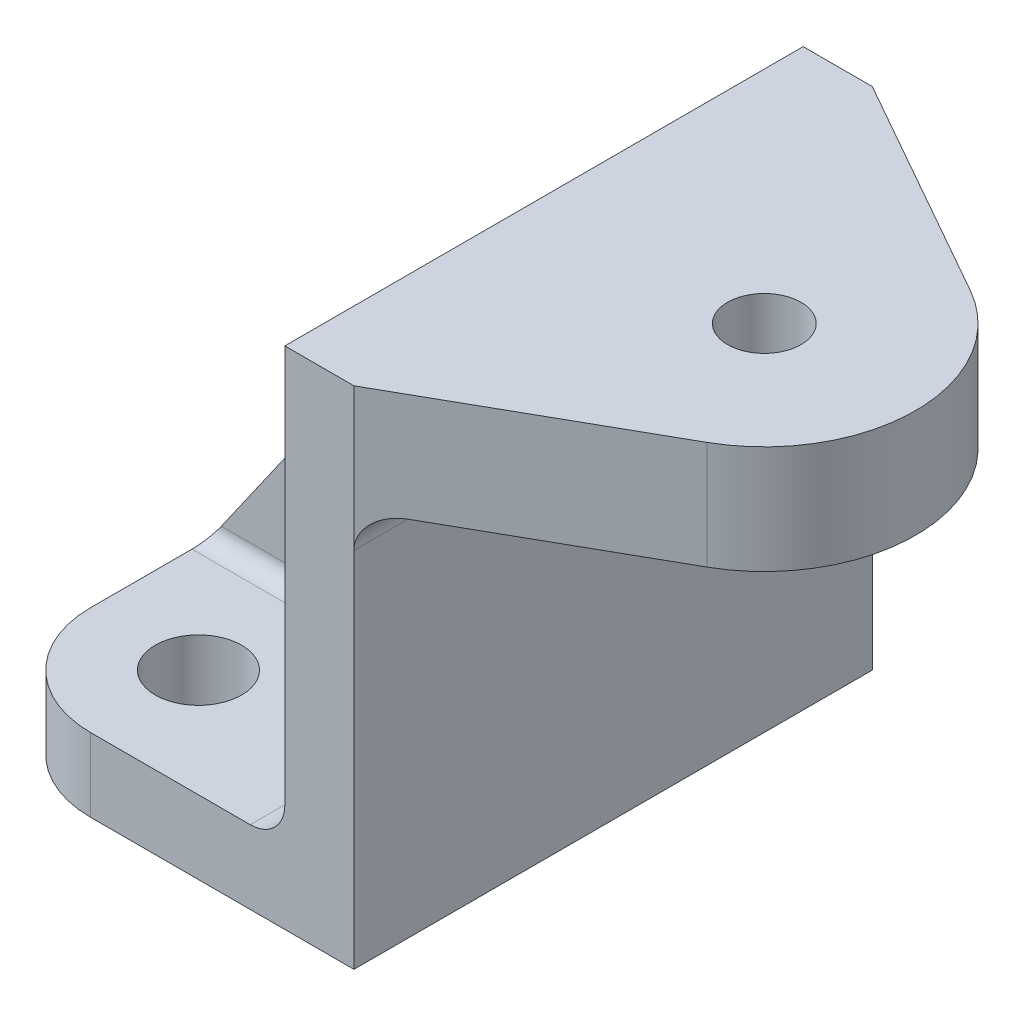
SolidWorks part; units mm, degrees
ref_plane "Front Plane" through (0, 0, 0) normal (0, 0, 1) x (1, 0, 0)
ref_plane "Top Plane" through (0, 0, 0) normal (0, 1, 0) x (1, 0, 0)
ref_plane "Right Plane" through (0, 0, 0) normal (1, 0, 0) x (0, 0, -1)
sketch "Sketch1" plane through (0, 0, 0) normal (0, 1, 0) x (1, 0, 0)
  line L1 (-30.5, 60) -> (30.5, 60)
  line L2 (-55.5, 35) -> (-55.5, -35)
  line L3 (-30.5, -60) -> (30.5, -60)
  line L4 (30.5, 60) -> (30.5, -60)
  circle A0 centre (-30.5, 35) radius 10
  circle A1 centre (-30.5, -35) radius 10
  arc A2 (-30.5, -60) -> (-55.5, -35) centre (-30.5, -35) cw
  arc A3 (-30.5, 60) -> (-55.5, 35) centre (-30.5, 35) ccw
  point P4 (-55.5, 0)
  point P5 (0, -60)
  point P11 (0, 0)
  point P16 (-55.5, 60)
  dimension "D3" = 20
  dimension "D4" = 25
  dimension "D5" = 25
  dimension "D6" = 25
  dimension "D7" = 25
  dimension "D1" = 120
  dimension "D2" = 86
extrude "Boss-Extrude1" add sketch "Sketch1" along normal blind 17
sketch "Sketch2" plane through (0, 17, 0) normal (0, 1, 0) x (1, 0, 0)
  line L0 (-30.5, -60) -> (30.5, -60) construction
  line L1 (30.5, 60) -> (14.5, 60)
  line L2 (30.5, 60) -> (30.5, -60)
  line L3 (30.5, -60) -> (14.5, -60)
  line L4 (14.5, 60) -> (14.5, -60)
  dimension "D1" = 16
extrude "Boss-Extrude2" add sketch "Sketch2" along normal blind 100
fillet "Fillet1" radius 8 1 edges at (14.5, 17, 0)
ref_plane "Plane1" through (0, 117, 0) normal (0, 1, 0) x (1, 0, 0)
sketch "Sketch3" plane through (0, 117, 0) normal (0, 1, 0) x (1, 0, 0)
  line L0 (30.5, -60) -> (30.5, 60) construction
  line L1 (30.5, 60) -> (82.728, 30.4663)
  line L2 (30.5, -60) -> (82.728, -30.4663)
  line L3 (30.5, -60) -> (30.5, 60)
  arc A0 (82.728, -30.4663) -> (82.728, 30.4663) centre (65.5, 0) ccw
  circle A1 centre (65.5, 0) radius 8.5
  dimension "D1" = 70
  dimension "D2" = 35
  dimension "D3" = 17
extrude "Boss-Extrude3" add sketch "Sketch3" against normal blind 25
ref_plane "Plane2" through (0, 0, 0) normal (0, 0, 1) x (1, 0, 0)
sketch "Sketch6" plane through (0, 0, 0) normal (0, 0, 1) x (1, 0, 0)
  line L0 (14.5, 117) -> (-55.5, 17)
rib "Rib2" sketch "Sketch6" sketch "Sketch6" thickness 15 extrusion direction parallel to sketch draft on no parameters "D1"=15
fillet "Fillet2" radius 4 6 edges at (-24.5, 17, -7.5) (12.1569, 19.3431, -7.5) (-24.5, 17, 7.5) (12.1569, 19.3431, 7.5) (14.5, 71, -7.5) (14.5, 71, 7.5)
fillet "Fillet3" radius 8 1 edges at (30.5, 92, 0)
